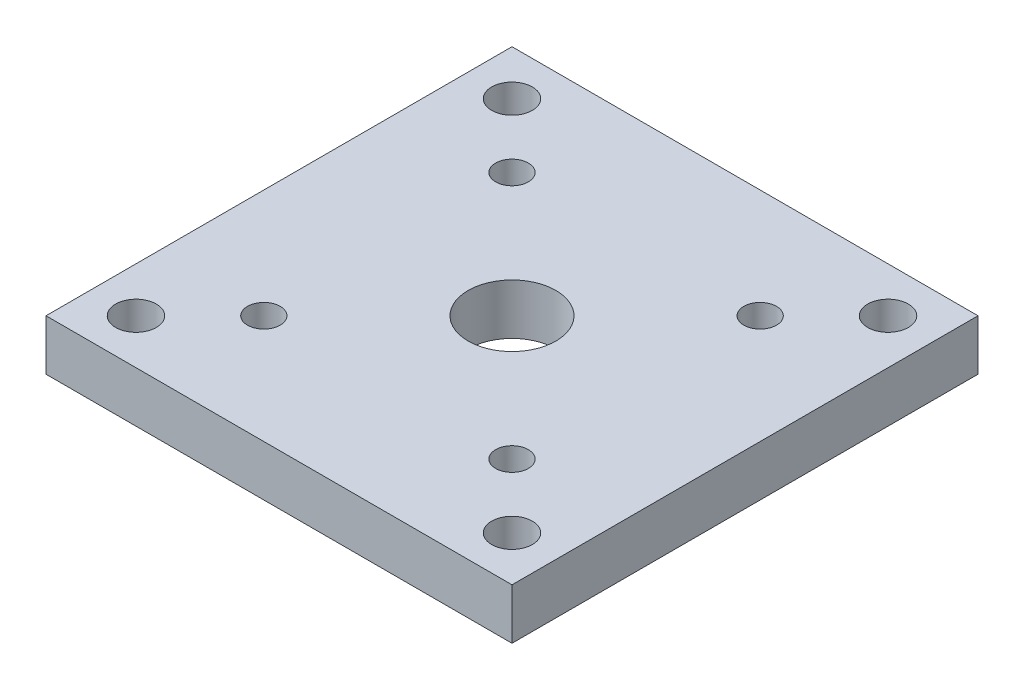
SolidWorks part; units mm, degrees
ref_plane "Top Plane" through (0, 0, 0) normal (0, 0, 1) x (1, 0, 0)
ref_plane "Front Plane" through (0, 0, 0) normal (0, 1, 0) x (1, 0, 0)
ref_plane "Right Plane" through (0, 0, 0) normal (1, 0, 0) x (0, 0, -1)
sketch "Sketch1" plane through (0, 0, 0) normal (0, 1, 0) x (1, 0, 0)
  line L0 (13.6537, 44.7663) -> (44.7663, 44.7663) construction
  line L1 (0, 0) -> (58.42, 0)
  line L2 (0, 0) -> (0, 58.42)
  line L3 (0, 58.42) -> (58.42, 58.42)
  line L4 (58.42, 0) -> (58.42, 58.42)
  line L5 (13.6537, 44.7663) -> (13.6537, 13.6537) construction
  line L6 (5.64, 52.78) -> (52.78, 52.78) construction
  line L7 (5.64, 52.78) -> (5.64, 5.64) construction
  line L8 (5.64, 5.64) -> (52.78, 5.64) construction
  line L9 (52.78, 52.78) -> (52.78, 5.64) construction
  line L10 (13.6537, 13.6537) -> (44.7663, 13.6537) construction
  line L11 (44.7663, 44.7663) -> (44.7663, 13.6537) construction
  line L12 (0, 58.42) -> (5.64, 52.78) construction
  line L13 (5.64, 52.78) -> (13.6537, 44.7663) construction
  line L14 (13.6537, 44.7663) -> (29.21, 29.21) construction
  line L15 (29.21, 29.21) -> (44.7663, 13.6537) construction
  line L16 (44.7663, 13.6537) -> (52.78, 5.64) construction
  line L17 (52.78, 5.64) -> (58.42, 0) construction
  circle A0 centre (5.64, 52.78) radius 2.55
  circle A1 centre (52.78, 52.78) radius 2.55
  circle A2 centre (52.78, 5.64) radius 2.55
  circle A3 centre (5.64, 5.64) radius 2.55
  circle A8 centre (29.21, 29.21) radius 5.5
  circle A9 centre (13.6537, 44.7663) radius 2.05
  circle A10 centre (44.7663, 44.7663) radius 2.05
  circle A11 centre (44.7663, 13.6537) radius 2.05
  circle A12 centre (13.6537, 13.6537) radius 2.05
  point P31 (24.4747, 9.2649)
  dimension "D1" = 58.42
  dimension "D4" = 5.1
  dimension "D5" = 11
  dimension "D6" = 4.1
  dimension "D2" = 47.14
  dimension "D3" = 44
extrude "Boss-Extrude1" add sketch "Sketch1" along normal blind 6.35
chamfer "Chamfer1" distance 2.48 angle 45 4 edges at (13.6537, 0, -42.7163) (44.7663, 0, -42.7163) (44.7663, 0, -11.6037) (13.6537, 0, -11.6037)
